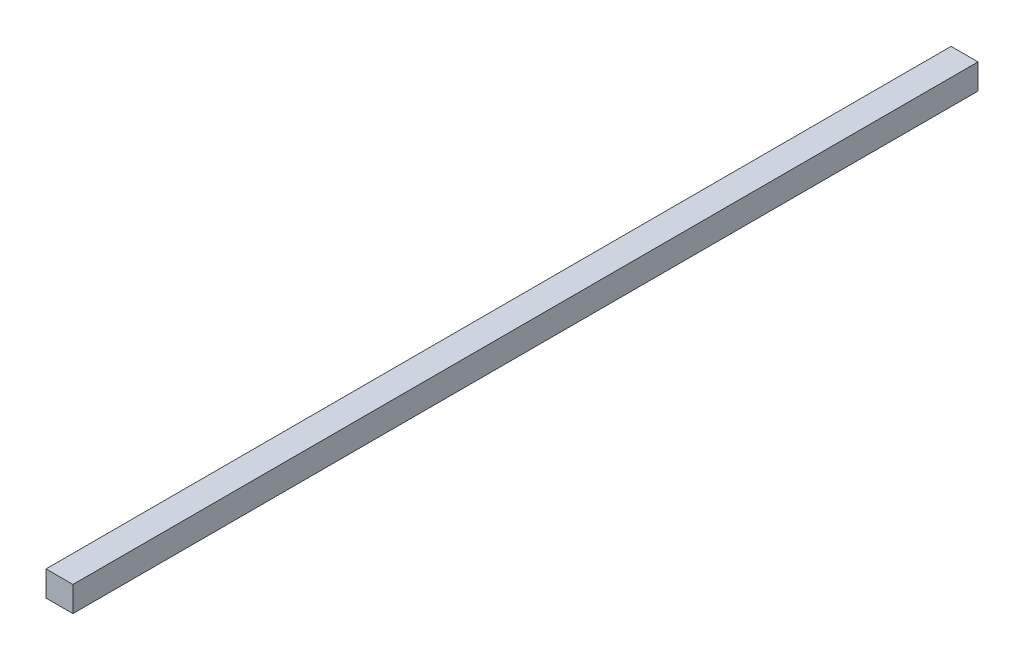
SolidWorks part; units mm, degrees
ref_plane "Front Plane" through (0, 0, 0) normal (0, 0, 1) x (1, 0, 0)
ref_plane "Top Plane" through (0, 0, 0) normal (0, 1, 0) x (1, 0, 0)
ref_plane "Right Plane" through (0, 0, 0) normal (1, 0, 0) x (0, 0, -1)
sketch "Sketch1" plane through (0, 0, 0) normal (0, 0, 1) x (1, 0, 0)
  line L1 (-33.7662, 17.8571) -> (16.2338, 17.8571)
  line L2 (-33.7662, 17.8571) -> (-33.7662, -29.1429)
  line L3 (-33.7662, -29.1429) -> (16.2338, -29.1429)
  line L4 (16.2338, 17.8571) -> (16.2338, -29.1429)
  dimension "D1" = 50
  dimension "D2" = 47
extrude "Boss-Extrude1" add sketch "Sketch1" along normal blind 1682
